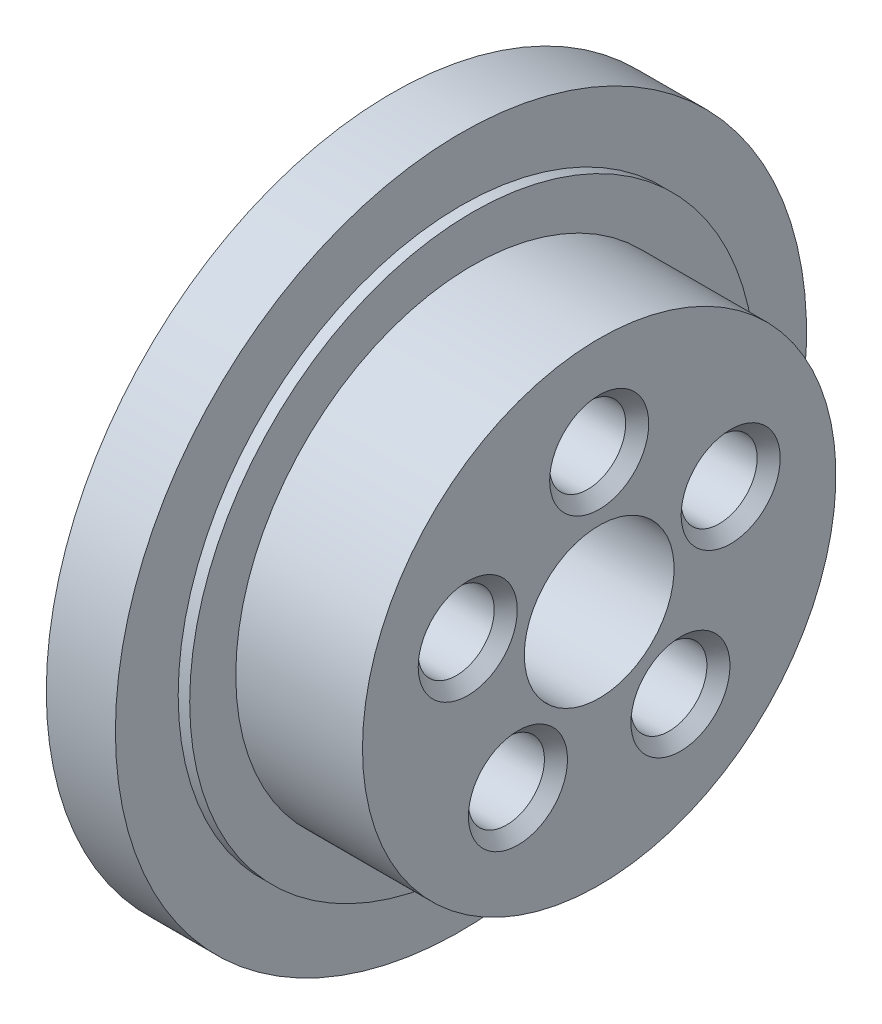
SolidWorks part; units mm, degrees
ref_plane "Front Plane" through (0, 0, 0) normal (0, 0, 1) x (1, 0, 0)
ref_plane "Top Plane" through (0, 0, 0) normal (0, 1, 0) x (1, 0, 0)
ref_plane "Right Plane" through (0, 0, 0) normal (1, 0, 0) x (0, 0, -1)
sketch "Sketch1" plane through (0, 0, 0) normal (0, 0, 1) x (1, 0, 0)
  line L0 (0, 30) -> (6, 30)
  line L9 (6, 30) -> (6, 24.55)
  line L10 (6, 24.55) -> (7, 24.55)
  line L11 (7, 24.55) -> (7, 20.55)
  line L12 (7, 20.55) -> (18, 20.55)
  line L13 (18, 20.55) -> (18, 6.5)
  line L14 (18, 6.5) -> (6, 6.5)
  line L15 (6, 6.5) -> (6, 7.5)
  line L16 (6, 7.5) -> (0, 7.5)
  line L17 (0, 7.5) -> (0, 30)
  line L18 (0, 0) -> (18, 0) construction
  dimension "D1" = 6
  dimension "D2" = 12
  dimension "D3" = 1
  dimension "D4" = 6
  dimension "D5" = 4
  dimension "D6" = 7.5
  dimension "D7" = 30
  dimension "D8" = 14.05
  dimension "D9" = 6.5
revolve "Revolve1" add sketch "Sketch1" angle 360 about L18
sketch "Sketch2" plane through (0, 0, 0) normal (-1, 0, 0) x (0, 0, 1)
  circle A0 centre (0, 0) radius 20 construction
  circle A1 centre (0, 20) radius 2.5
  circle A2 centre (17.3205, 10) radius 2.5
  circle A3 centre (17.3205, -10) radius 2.5
  circle A4 centre (0, -20) radius 2.5
  circle A5 centre (-17.3205, -10) radius 2.5
  circle A6 centre (-17.3205, 10) radius 2.5
  point P18 (0, 0)
  dimension "D1" = 40
  dimension "D2" = 5
extrude "Cut-Extrude1" cut sketch "Sketch2" against normal blind 4.5
sketch "Sketch3" plane through (18, 0, 0) normal (1, 0, 0) x (0, 0, -1)
  circle A0 centre (0, 0) radius 12 construction
  circle A3 centre (0, 12) radius 3.3
  circle A6 centre (11.4127, 3.7082) radius 3.3
  circle A7 centre (7.0534, -9.7082) radius 3.3
  circle A8 centre (-7.0534, -9.7082) radius 3.3
  circle A9 centre (-11.4127, 3.7082) radius 3.3
  point P15 (0, 0)
  dimension "D1" = 24
  dimension "D2" = 6.6
extrude "Cut-Extrude2" cut sketch "Sketch3" against normal blind 10.5
chamfer "Chamfer1" distance 1 angle 45 5 edges at (18, 3.7082, 8.1127) (18, -9.7082, 3.7534) (18, -9.7082, -10.3534) (18, 3.7082, -14.7127) (18, 12, -3.3)
sketch "Sketch4" [suppressed] plane through (6, 0, 0) normal (-1, 0, 0) x (0, 0, 1)
  circle A0 centre (0, 0) radius 6.5
  dimension "D1" = 13
extrude "Cut-Extrude3" [suppressed] cut sketch "Sketch4" against normal through all
equation "\"R_ROLL\"= 5mm"
equation "\"D_SUN\"= 80mm"
equation "\"NUM_ROLL\"= 16"
equation "\"RHO\"= 1mm"
equation "\"D_SHAFT\"= 15mm"
equation "\"D_OUTPUT\"= 40mm"
equation "\"NUM_OUT\"= 6"
equation "\"R_OUT_ROLL\"= 5mm"
equation "\"D1@Sketch2\"=\"D_OUTPUT\""
